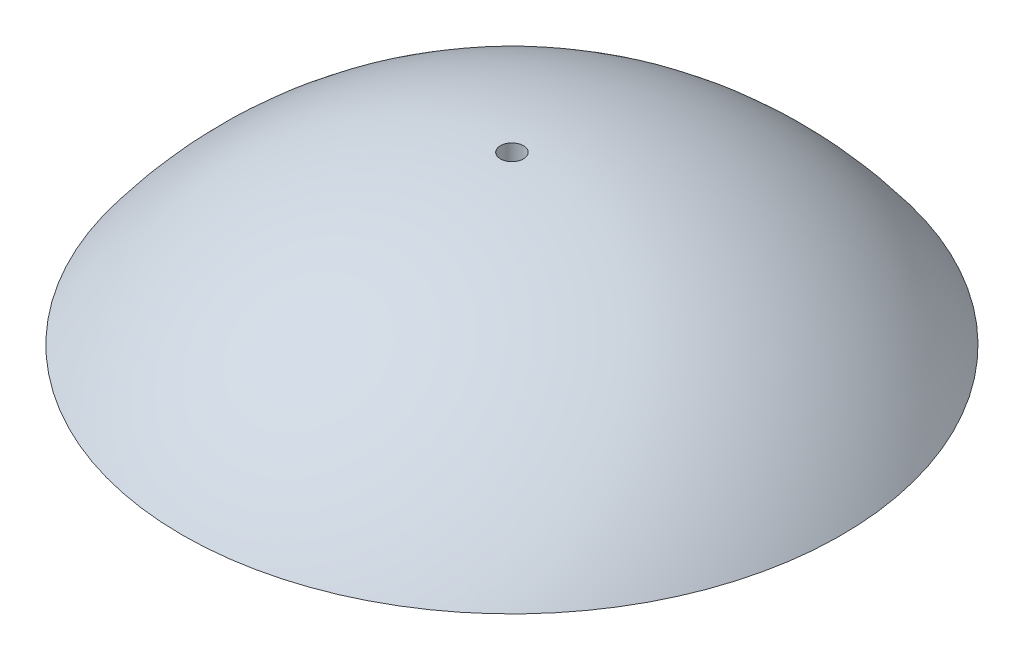
SolidWorks part; units mm, degrees
ref_plane "Front Plane" through (0, 0, 0) normal (0, 0, 1) x (1, 0, 0)
ref_plane "Top Plane" through (0, 0, 0) normal (0, 1, 0) x (1, 0, 0)
ref_plane "Right Plane" through (0, 0, 0) normal (1, 0, 0) x (0, 0, -1)
sketch "Sketch2" plane through (0, 0, 0) normal (1, 0, 0) x (0, 0, -1)
  line L0 (-33.8, 0) -> (0, 0)
  line L1 (0, 0) -> (0, 33.8) construction
  line L2 (-27.2478, 20) -> (0, 20)
  line L4 (-0.95, 33.7866) -> (-0.95, 20)
  arc A0 (-33.8, 0) -> (0, 33.8) centre (0, 0) cw
  arc A1 (-31.8, 0) -> (0, 31.8) centre (0, 0) cw
  dimension "D1" = 67.6
  dimension "D3" = 20
  dimension "D4" = 1.9
  dimension "D5" = 2
revolve "Revolve1" add sketch "Sketch2" angle 360 about L1
sketch "Sketch3" plane through (0, 20, 0) normal (0, -1, 0) x (1, 0, 0)
  line L0 (0, 23.1143) -> (0, 0)
  line L1 (0, 0) -> (16.5136, 16.1733)
  line L2 (23.1143, 0) -> (0, 0)
  line L3 (0, -23.1143) -> (0, 0)
  line L4 (0, 0) -> (-16.5128, -16.174)
  line L5 (-23.1143, 0) -> (0, 0)
  line L6 (-16.5128, 16.174) -> (0, 0.2323)
  line L7 (0, 0) -> (15.2603, -17.3608)
  circle A0 centre (0, 0) radius 26.75
  circle A1 centre (0, 0) radius 23.1143
  circle A2 centre (0, 0) radius 7.397
  dimension "D1" = 53.5
extrude "Boss-Extrude1" [suppressed] add sketch "Sketch3" along normal blind 23 separate body
